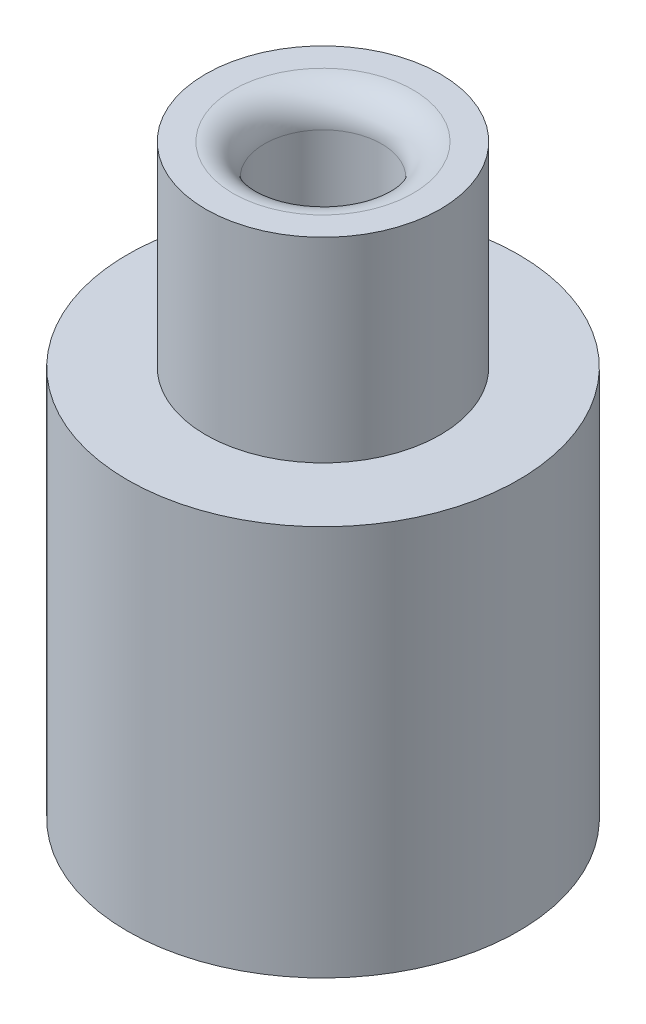
SolidWorks part; units mm, degrees
ref_plane "Front Plane" through (0, 0, 0) normal (0, 0, 1) x (1, 0, 0)
ref_plane "Top Plane" through (0, 0, 0) normal (0, 1, 0) x (1, 0, 0)
ref_plane "Right Plane" through (0, 0, 0) normal (1, 0, 0) x (0, 0, -1)
sketch "Esquisse1" plane through (0, 0, 0) normal (0, 1, 0) x (1, 0, 0)
  circle A0 centre (0, 0) radius 5
extrude "Boss.-Extru.1" add sketch "Esquisse1" along normal blind 6 and the other way blind 4
sketch "Esquisse2" plane through (0, 6, 0) normal (0, 1, 0) x (1, 0, 0)
  circle A0 centre (0, 0) radius 3
extrude "Boss.-Extru.2" add sketch "Esquisse2" along normal blind 5 and the other way blind 1
sketch "Esquisse3" plane through (0, 11, 0) normal (0, 1, 0) x (1, 0, 0)
  circle A0 centre (0, 0) radius 1.5
extrude "Enlèv. mat.-Extru.2" cut sketch "Esquisse3" against normal blind 6
sketch "Esquisse4" plane through (0, -4, 0) normal (0, -1, 0) x (1, 0, 0)
  circle A0 centre (0, 0) radius 2.5
extrude "Enlèv. mat.-Extru.3" cut sketch "Esquisse4" against normal blind 5
fillet "Congé1" radius 0.8 1 edges at (0, 11, 1.5)
